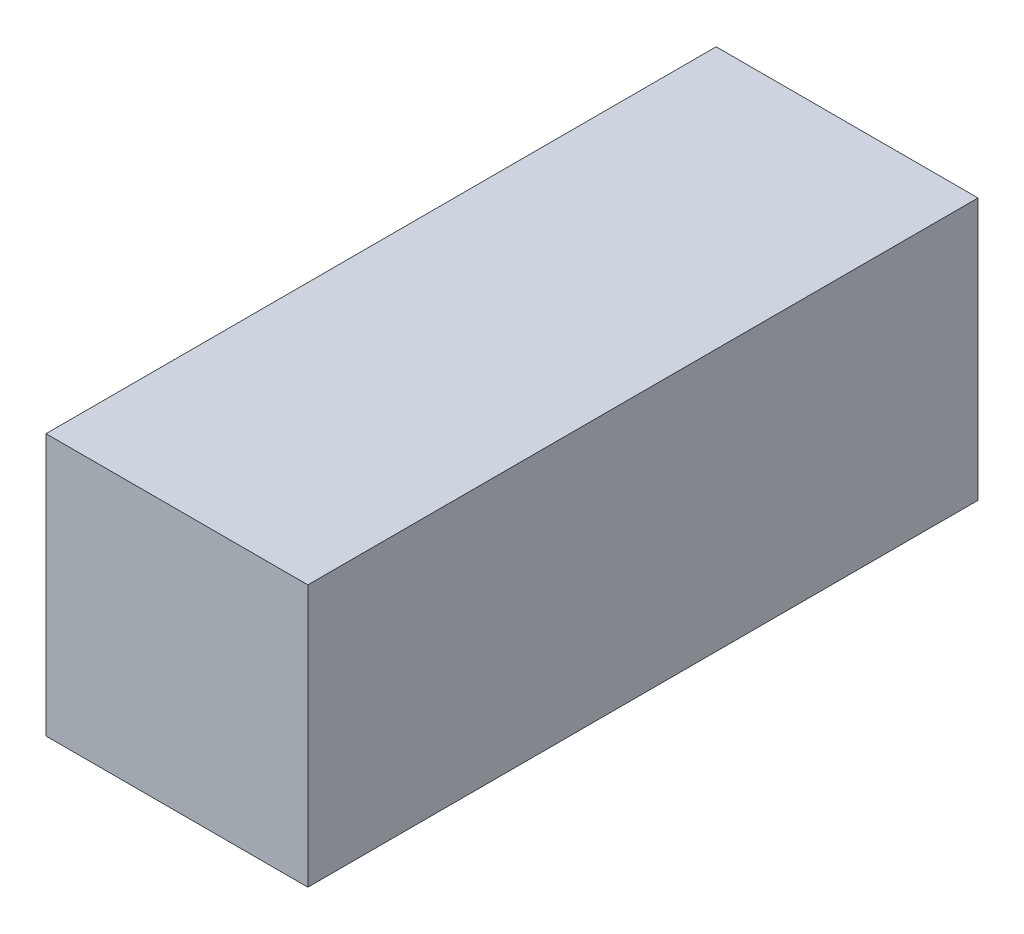
SolidWorks part; units mm, degrees
ref_plane "Front Plane" through (0, 0, 0) normal (0, 0, 1) x (1, 0, 0)
ref_plane "Top Plane" through (0, 0, 0) normal (0, 1, 0) x (1, 0, 0)
ref_plane "Right Plane" through (0, 0, 0) normal (1, 0, 0) x (0, 0, -1)
sketch "Sketch1" plane through (0, 0, 0) normal (0, 0, 1) x (1, 0, 0)
  line L0 (0, 33.7911) -> (0, -32.5815) construction
  line L1 (-54.1262, 0) -> (54.2774, 0) construction
  line L3 (-12.7, 12.7) -> (12.7, 12.7)
  line L4 (-12.7, 12.7) -> (-12.7, -12.7)
  line L5 (-12.7, -12.7) -> (12.7, -12.7)
  line L6 (12.7, 12.7) -> (12.7, -12.7)
  dimension "D1" = 25.4
  dimension "D2" = 25.4
  dimension "D3" = 12.7
  dimension "D4" = 12.7
extrude "Boss-Extrude1" add sketch "Sketch1" along normal blind 65
